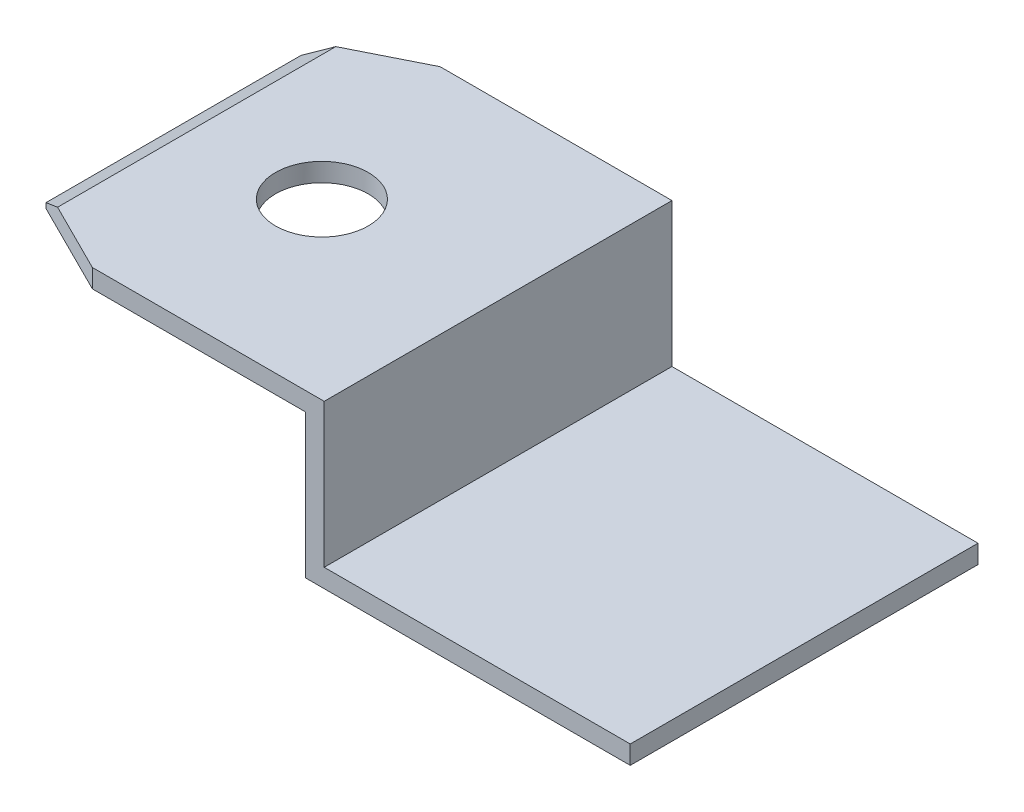
SolidWorks part; units mm, degrees
ref_plane "Front Plane" through (0, 0, 0) normal (0, 0, 1) x (1, 0, 0)
ref_plane "Top Plane" through (0, 0, 0) normal (0, 1, 0) x (1, 0, 0)
ref_plane "Right Plane" through (0, 0, 0) normal (1, 0, 0) x (0, 0, -1)
sketch "Sketch1" plane through (0, 0, 0) normal (0, 0, 1) x (1, 0, 0)
  line L0 (0, 0) -> (70, 0)
  line L1 (70, 0) -> (70, -31)
  line L2 (70, -31) -> (136, -31)
  line L3 (136, -31) -> (136, -35)
  line L4 (136, -35) -> (66, -35)
  line L5 (66, -35) -> (66, -4)
  line L6 (66, -4) -> (0, -4)
  line L7 (0, -4) -> (0, 0)
  dimension "D1" = 4
  dimension "D2" = 4
  dimension "D3" = 4
  dimension "D4" = 70
  dimension "D5" = 70
  dimension "D6" = 35
extrude "Boss-Extrude1" add sketch "Sketch1" along normal blind 75
sketch "Sketch2" plane through (0, 0, 0) normal (0, 1, 0) x (1, 0, 0)
  line L0 (0, -37.5) -> (70, -37.5) construction
  line L1 (0, -75) -> (0, 0) construction
  line L2 (70, -75) -> (70, 0) construction
  circle A0 centre (32, -37.5) radius 10
  dimension "D1" = 32
  dimension "D2" = 20
extrude "Cut-Extrude1" cut sketch "Sketch2" against normal through all
chamfer "Chamfer1" distance 10 distance2 20 1 edges at (0, -2, 75)
chamfer "Chamfer2" distance 20 distance2 10 1 edges at (0, -2, 0)
chamfer "Chamfer3" distance 5 angle 30 1 edges at (0, 0, 37.5)
